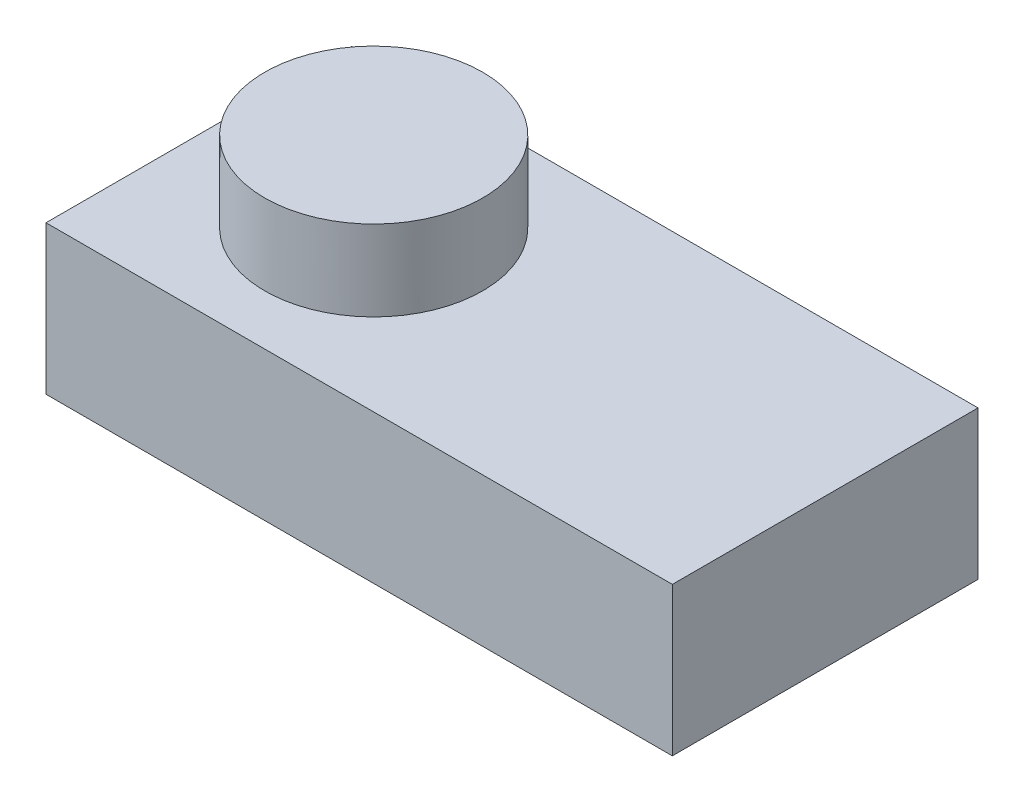
SolidWorks part; units mm, degrees
ref_plane "Ön Düzlem" through (0, 0, 0) normal (0, 0, 1) x (1, 0, 0)
ref_plane "Üst Düzlem" through (0, 0, 0) normal (0, 1, 0) x (1, 0, 0)
ref_plane "Sağ Düzlem" through (0, 0, 0) normal (1, 0, 0) x (0, 0, -1)
sketch "Çizim1" plane through (0, 0, 0) normal (0, 0, 1) x (1, 0, 0)
  line L3 (-12.5482, 14.1673) -> (88.6468, 14.1673)
  line L4 (-12.5482, 14.1673) -> (-12.5482, -35.2159)
  line L5 (-12.5482, -35.2159) -> (88.6468, -35.2159)
  line L6 (88.6468, 14.1673) -> (88.6468, -35.2159)
extrude "Yükseklik-Ekstrüzyon2" add sketch "Çizim1" along normal blind 24
move or copy body "Gövde-Taşı/Kopyala1" bodies to move or copy 102 copy no rotation origin (0, -10.5243, 12) rotation axis (1, 0, 0) rotation angle 90
sketch "Çizim2" plane through (0, 1.4757, 0) normal (0, 1, 0) x (1, 0, 0)
  circle A0 centre (14.6592, -10.9507) radius 17.6095
extrude "Yükseklik-Ekstrüzyon4" add sketch "Çizim2" along normal blind 13
